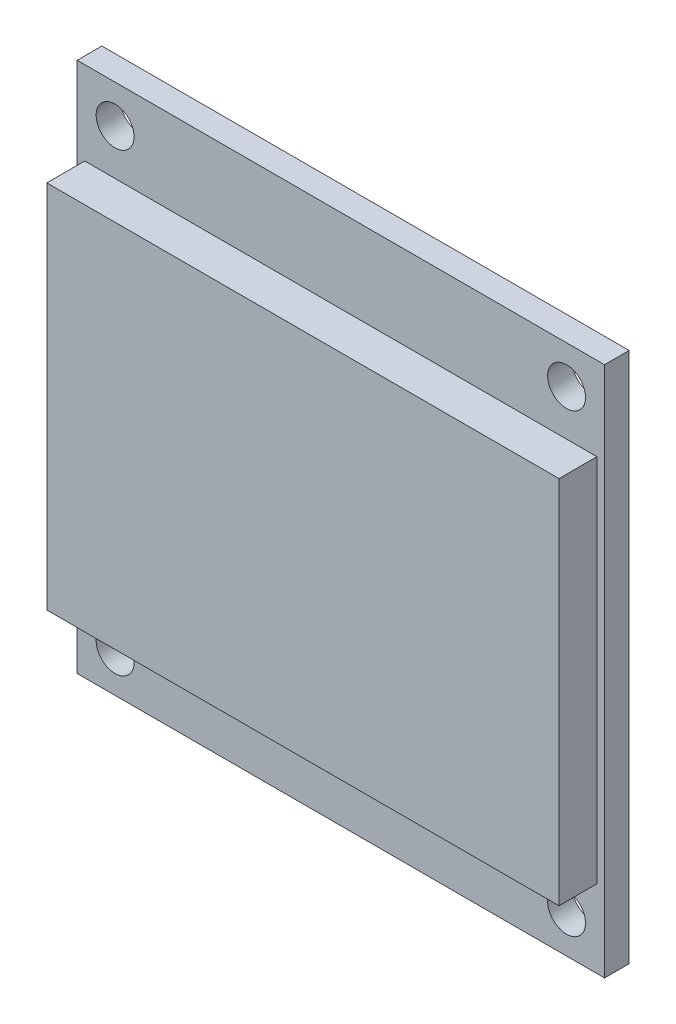
SolidWorks part; units mm, degrees
ref_plane "Front Plane" through (0, 0, 0) normal (0, 0, 1) x (1, 0, 0)
ref_plane "Top Plane" through (0, 0, 0) normal (0, 1, 0) x (1, 0, 0)
ref_plane "Right Plane" through (0, 0, 0) normal (1, 0, 0) x (0, 0, -1)
sketch "Sketch1" plane through (0, 0, 0) normal (0, 0, 1) x (1, 0, 0)
  line L1 (0, 0) -> (27.8, 0)
  line L2 (0, 0) -> (0, 28)
  line L3 (0, 28) -> (27.8, 28)
  line L4 (27.8, 0) -> (27.8, 28)
  circle A0 centre (25.8, 26) radius 1
  circle A1 centre (2, 26) radius 1
  circle A2 centre (25.8, 2) radius 1
  circle A3 centre (2, 2) radius 1
  dimension "D6" = 2
  dimension "D1" = 27.8
  dimension "D2" = 28
  dimension "D3" = 2
  dimension "D4" = 23.8
  dimension "D5" = 24
  dimension "D7" = 2
extrude "Boss-Extrude1" add sketch "Sketch1" along normal blind 1.3
sketch "Sketch2" plane through (0, 0, 1.3) normal (0, 0, 1) x (1, 0, 0)
  line L0 (0, 28) -> (0, 0) construction
  line L1 (0.4, 23.6) -> (27.4, 23.6)
  line L2 (0.4, 23.6) -> (0.4, 4.1)
  line L3 (0.4, 4.1) -> (27.4, 4.1)
  line L4 (27.4, 23.6) -> (27.4, 4.1)
  line L6 (27.8, 28) -> (0, 28) construction
  dimension "D1" = 19.5
  dimension "D2" = 27
  dimension "D3" = 0.4
  dimension "D4" = 4.4
extrude "Boss-Extrude2" add sketch "Sketch2" along normal blind 2
